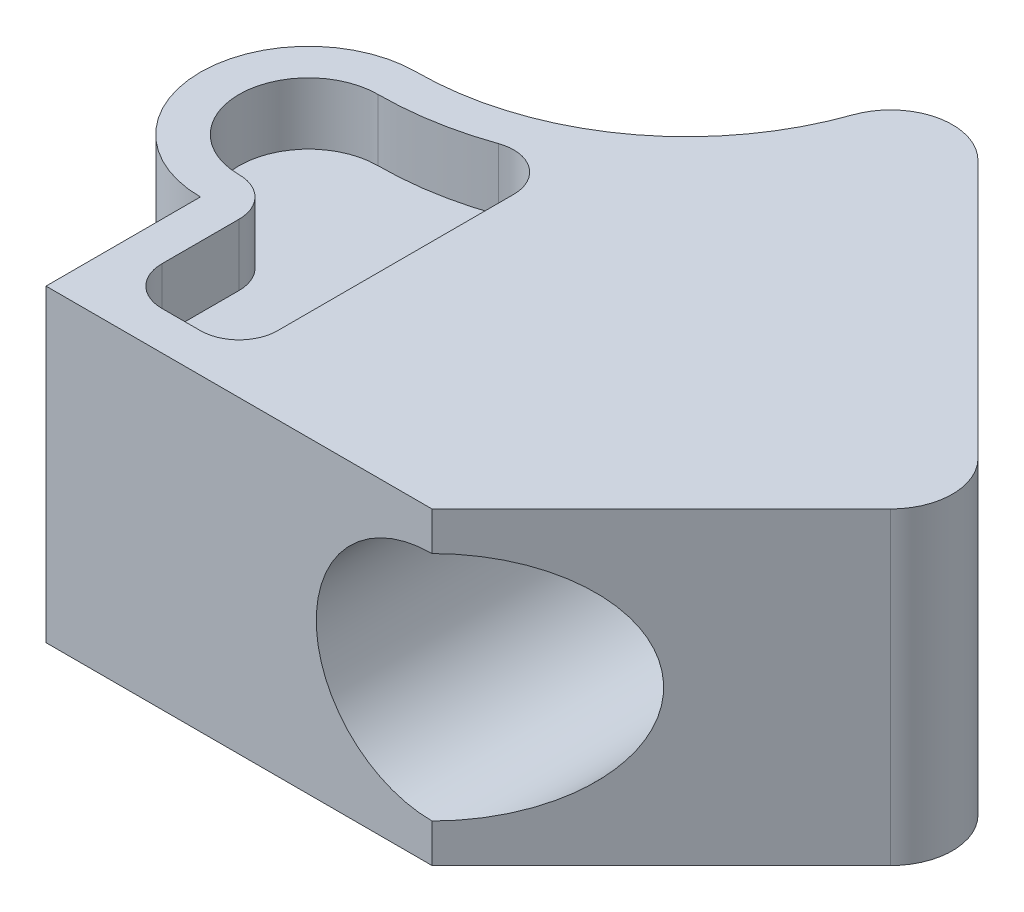
SolidWorks part; units mm, degrees
material "Alliage 1060"
ref_plane "Plan de face" through (0, 0, 0) normal (0, 0, 1) x (1, 0, 0)
ref_plane "Plan de dessus" through (0, 0, 0) normal (0, 1, 0) x (1, 0, 0)
ref_plane "Plan de droite" through (0, 0, 0) normal (1, 0, 0) x (0, 0, -1)
sketch "Esquisse1" plane through (0, 0, 0) normal (0, 1, 0) x (1, 0, 0)
  line L0 (0, 0) -> (50, 0)
  line L1 (50, 0) -> (79.6985, 29.6985)
  line L2 (0, 0) -> (0, 20)
  line L3 (79.6985, 41.0122) -> (46.2469, 74.4637)
  arc A0 (0, 20) -> (0, 48) centre (0, 34) cw
  arc A1 (0, 48) -> (33.0384, 71.4475) centre (0, 83) ccw
  arc A2 (79.6985, 29.6985) -> (79.6985, 41.0122) centre (74.0416, 35.3553) ccw
  arc A3 (46.2469, 74.4637) -> (33.0384, 71.4475) centre (40.5901, 68.8069) ccw
  point P10 (0, 0)
  point P11 (11.1784, 80.9921)
  point P12 (0, 0)
  point P13 (0, 0)
  point P14 (-6.1734, 81.5654)
  point P15 (0, 0)
  point P17 (85.3553, 35.3553)
  dimension "D4" = 20
  dimension "D5" = 14
  dimension "D7" = 70
  dimension "D8" = 8
  dimension "D3" = 135
  dimension "D6" = 90
  dimension "D1" = 50
  dimension "D2" = 50
extrude "Boss.-Extru.1" add sketch "Esquisse1" along normal mid plane 40
sketch "Esquisse2" plane through (0, 20, 0) normal (0, 1, 0) x (1, 0, 0)
  line L6 (20, 20) -> (20, 0)
  line L7 (20, 40.5736) -> (20, 10)
  line L8 (5, 26.5167) -> (5, 5)
  line L9 (5, 5) -> (47.9289, 5)
  line L10 (47.9289, 5) -> (76.163, 33.234)
  line L11 (76.163, 37.4767) -> (42.7114, 70.9282)
  line L12 (5, 20) -> (5, 10)
  line L13 (10, 5) -> (15, 5)
  arc A4 (13.3333, 45.2876) -> (20, 40.5736) centre (15, 40.5736) cw
  arc A5 (15, 5) -> (20, 10) centre (15, 10) ccw
  arc A6 (5, 10) -> (10, 5) centre (10, 10) ccw
  arc A7 (5, 20) -> (0, 25) centre (0, 20) ccw
  arc A8 (76.163, 33.234) -> (76.163, 37.4767) centre (74.0416, 35.3553) ccw
  arc A9 (42.7114, 70.9282) -> (37.7582, 69.7971) centre (40.5901, 68.8069) ccw
  arc A10 (0, 43) -> (37.7582, 69.7971) centre (0, 83) ccw
  arc A11 (0, 43) -> (5, 26.5167) centre (0, 34) ccw
  arc A14 (0, 43) -> (13.3333, 45.2876) centre (0, 83) ccw
  arc A15 (0, 43) -> (0, 25) centre (0, 34) ccw
  point P0 (20.2566, 60.4495)
  dimension "D3" = 5
  dimension "D1" = 5
  dimension "D2" = 20
extrude "Enlèv. mat.-Extru.1" cut sketch "Esquisse2" against normal blind 8
sketch "Esquisse3" plane through (0, 0, 0) normal (0, 0, 1) x (1, 0, 0)
  line L0 (-14, 20) -> (-14, -20) construction
  line L1 (50, -20) -> (79.6985, -20) construction
  circle A0 centre (50, 0) radius 15
  circle A1 centre (-14, 0) radius 10
  dimension "D4" = 20
  dimension "D1" = 30
  dimension "D2" = 64
  dimension "D3" = 20
extrude "Enlèv. mat.-Extru.2" cut sketch "Esquisse3" against normal through all
equation "\"A\"= 50"
equation "\"B\"= 10"
equation "\"C\"= \"B\" + 20"
equation "\"D4@Esquisse3\"=\"B\" * 2"
equation "\"D1@Esquisse1\"=\"A\""
equation "\"D1@Esquisse3\"=\"C\""
equation "\"D2@Esquisse1\"=\"A\""
